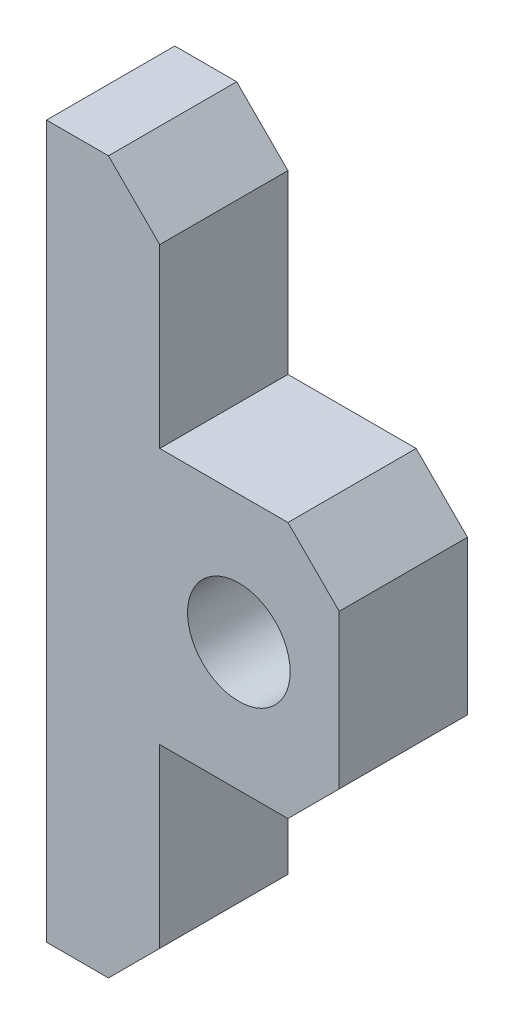
SolidWorks part; units mm, degrees
ref_plane "Спереди" through (0, 0, 0) normal (0, 0, 1) x (1, 0, 0)
ref_plane "Сверху" through (0, 0, 0) normal (0, 1, 0) x (1, 0, 0)
ref_plane "Справа" through (0, 0, 0) normal (1, 0, 0) x (0, 0, -1)
sketch "Эскиз1" plane through (0, 0, 0) normal (1, 0, 0) x (0, 0, -1)
  line L1 (-20, -12.8602) -> (-10, -12.8602)
  line L2 (-20, -12.8602) -> (-20, -68.4009)
  line L3 (-20, -68.4009) -> (-10, -68.4009)
  line L4 (-10, -12.8602) -> (-10, -68.4009)
  point P0 (0, 0)
extrude "Вытянуть1" add sketch "Эскиз1" along normal blind 25
sketch "Эскиз2" plane through (25, 0, 0) normal (1, 0, 0) x (0, 0, -1)
  line L0 (0, 52.2153) -> (0, 56.4881) construction
  line L2 (-10, -12.8602) -> (-20, -12.8602) construction
  line L3 (-24.675, 17.5522) -> (-5.325, 17.5522)
  line L4 (-24.675, 17.5522) -> (-24.675, -43.2725)
  line L5 (-24.675, -43.2725) -> (-5.325, -43.2725)
  line L6 (-5.325, 17.5522) -> (-5.325, -43.2725)
  line L7 (-24.675, 17.5522) -> (-5.325, -43.2725) construction
  line L8 (-24.675, -43.2725) -> (-5.325, 17.5522) construction
  point P1 (-15, -12.8602)
sketch "Эскиз5" plane through (0, 0, 20) normal (0, 0, 1) x (1, 0, 0)
  line L0 (0, -12.8602) -> (0, -68.4009) construction
  circle A0 centre (15, -40.6306) radius 4
  dimension "D1" = 15
extrude "Вырез-Вытянуть2" cut sketch "Эскиз5" against normal through all
sketch "Эскиз6" plane through (0, 0, 20) normal (0, 0, 1) x (1, 0, 0)
  line L0 (25, -40.6306) -> (39.1349, -40.6306) construction
  line L2 (22.8286, -50.6306) -> (22.8286, -30.6306)
  line L3 (22.8286, -30.6306) -> (8.8286, -30.6306)
  line L4 (8.8286, -30.6306) -> (8.8286, -12.8602)
  line L5 (8.8286, -12.8602) -> (25, -12.8602)
  line L6 (25, -12.8602) -> (0, -12.8602) construction
  line L7 (25, -12.8602) -> (25, -68.4009) construction
  line L8 (25, -12.8602) -> (25, -68.4009)
  line L9 (8.8286, -50.6306) -> (8.8286, -68.4009)
  line L10 (8.8286, -68.4009) -> (25, -68.4009)
  line L11 (22.8286, -50.6306) -> (8.8286, -50.6306)
  point P1 (25, -40.6306)
  point P16 (22.8286, -40.6306)
extrude "Вырез-Вытянуть3" cut sketch "Эскиз6" against normal through all
chamfer "Фаска1" distance 4 angle 45 4 edges at (8.8286, -68.4009, 15) (8.8286, -12.8602, 15) (22.8286, -30.6306, 15) (22.8286, -50.6306, 15)
